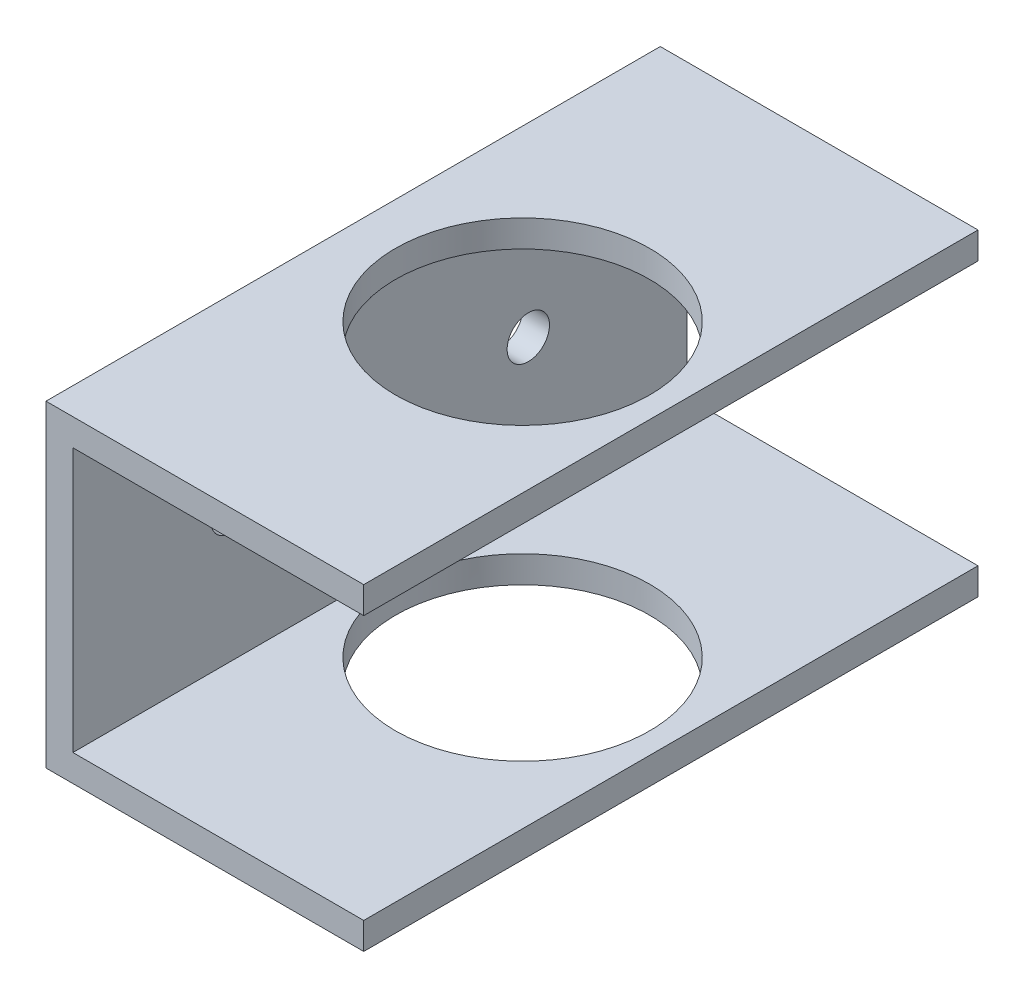
SolidWorks part; units mm, degrees
ref_plane "Front Plane" through (0, 0, 0) normal (0, 0, 1) x (1, 0, 0)
ref_plane "Top Plane" through (0, 0, 0) normal (0, 1, 0) x (1, 0, 0)
ref_plane "Right Plane" through (0, 0, 0) normal (1, 0, 0) x (0, 0, -1)
sketch "Sketch1" plane through (0, 0, 0) normal (0, 0, 1) x (1, 0, 0)
  line L0 (0, -37.5) -> (0, 37.5)
  line L1 (0, 37.5) -> (75, 37.5)
  line L2 (75, 37.5) -> (75, 31.15)
  line L3 (75, 31.15) -> (6.35, 31.15)
  line L4 (6.35, 31.15) -> (6.35, -31.15)
  line L5 (6.35, -31.15) -> (75, -31.15)
  line L6 (75, -31.15) -> (75, -37.5)
  line L7 (75, -37.5) -> (0, -37.5)
  line L8 (0, 0) -> (6.35, 0) construction
  dimension "D1" = 75
  dimension "D2" = 75
  dimension "D3" = 6.35
extrude "Boss-Extrude1" add sketch "Sketch1" along normal blind 145
sketch "Sketch2" plane through (0, 37.5, 0) normal (0, 1, 0) x (1, 0, 0)
  line L0 (40, -72.5) -> (0, -72.5) construction
  line L1 (0, -145) -> (0, 0) construction
  circle A0 centre (40, -72.5) radius 30
  dimension "D2" = 60
  dimension "D1" = 40
extrude "Cut-Extrude1" cut sketch "Sketch2" against normal through all
sketch "Sketch3" plane through (6.35, 0, 0) normal (1, 0, 0) x (0, 0, -1)
  line L0 (-107.5, 0) -> (-37.5, 0) construction
  line L2 (-145, 31.15) -> (0, 31.15) construction
  line L3 (-72.5, 31.15) -> (-72.5, -31.15) construction
  line L4 (-145, -31.15) -> (0, -31.15) construction
  circle A0 centre (-107.5, 0) radius 5
  circle A1 centre (-37.5, 0) radius 5
  point P4 (-72.5, 0)
  dimension "D1" = 10
  dimension "D2" = 70
extrude "Cut-Extrude2" cut sketch "Sketch3" against normal blind 10
